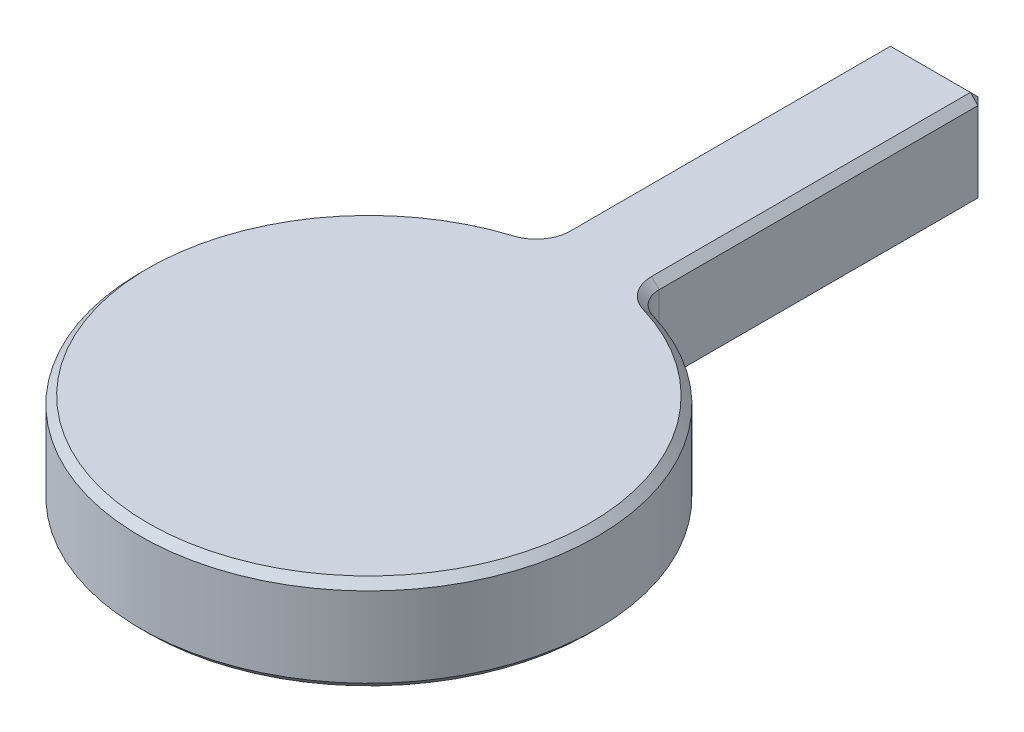
SolidWorks part; units mm, degrees
ref_plane "前视基准面" through (0, 0, 0) normal (0, 0, 1) x (1, 0, 0)
ref_plane "上视基准面" through (0, 0, 0) normal (0, 1, 0) x (1, 0, 0)
ref_plane "右视基准面" through (0, 0, 0) normal (1, 0, 0) x (0, 0, -1)
other "Configuration Table"
sketch "草图1" plane through (0, 0, 0) normal (0, 1, 0) x (1, 0, 0)
  line L3 (-0.1, 30) -> (-2.6, 30)
  line L4 (-2.6, 11.7149) -> (-2.6, 30)
  line L7 (-0.1, 30) -> (2.4, 30)
  line L8 (2.4, 11.7576) -> (2.4, 30)
  arc A0 (-2.6, 11.7149) -> (2.4, 11.7576) centre (0, 0) ccw
  dimension "D1" = 24
  dimension "D2" = 2.5
  dimension "D3" = 2.5
  dimension "D4" = 30
extrude "凸台-拉伸1" add sketch "草图1" along normal blind 5
fillet "圆角1" radius 1.4 2 edges at (2.4, 2.5, -11.7576) (-2.6, 2.5, -11.7149)
chamfer "倒角1" distance 0.4 angle 45 14 edges at (2.4, 2.5, -30) (2.4, 0, -21.425) (-0.1, 0, -30) (0.0936, 0, 11.9996) (-2.6, 0, -21.3945) (-2.6, 2.5, -30) (-2.6, 5, -21.3945) (-0.1, 5, -30) (2.4, 5, -21.425) (0.0936, 5, 11.9996) (2.6784, 0, -12.012) (-2.8719, 0, -11.9599) (2.6784, 5, -12.012) (-2.8719, 5, -11.9599)
